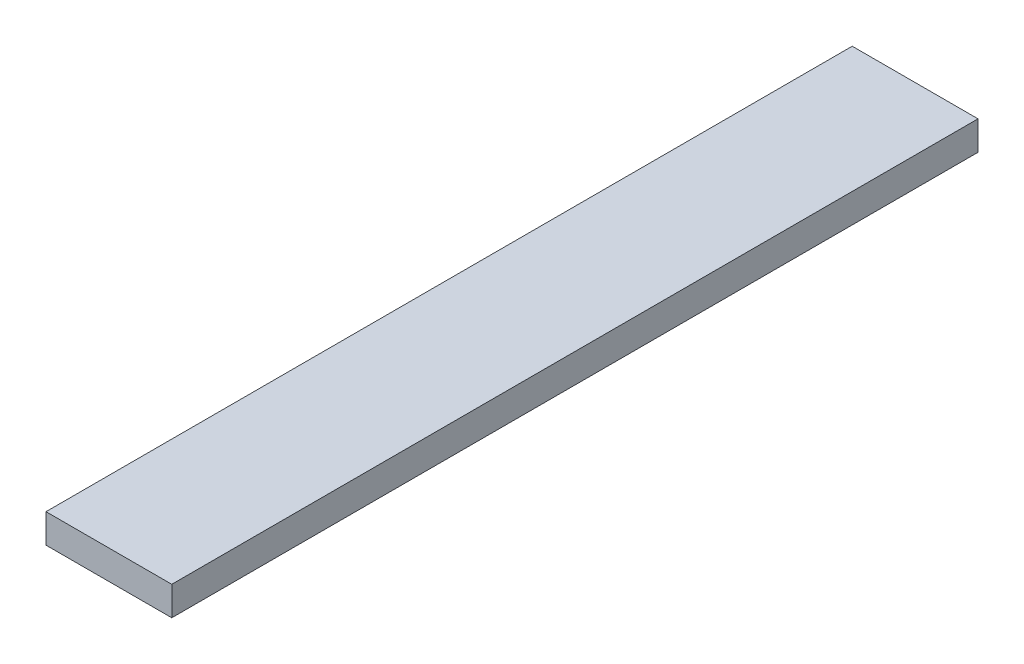
SolidWorks part; units mm, degrees
ref_plane "Front Plane" through (0, 0, 0) normal (0, 0, 1) x (1, 0, 0)
ref_plane "Top Plane" through (0, 0, 0) normal (0, 1, 0) x (1, 0, 0)
ref_plane "Right Plane" through (0, 0, 0) normal (1, 0, 0) x (0, 0, -1)
sketch "Sketch1" plane through (0, 0, 0) normal (0, 0, 1) x (1, 0, 0)
  line L1 (0, 0) -> (78, 0)
  line L2 (0, 0) -> (0, 18)
  line L3 (0, 18) -> (78, 18)
  line L4 (78, 0) -> (78, 18)
  dimension "D1" = 78
  dimension "D2" = 18
extrude "Boss-Extrude1" add sketch "Sketch1" along normal blind 500
